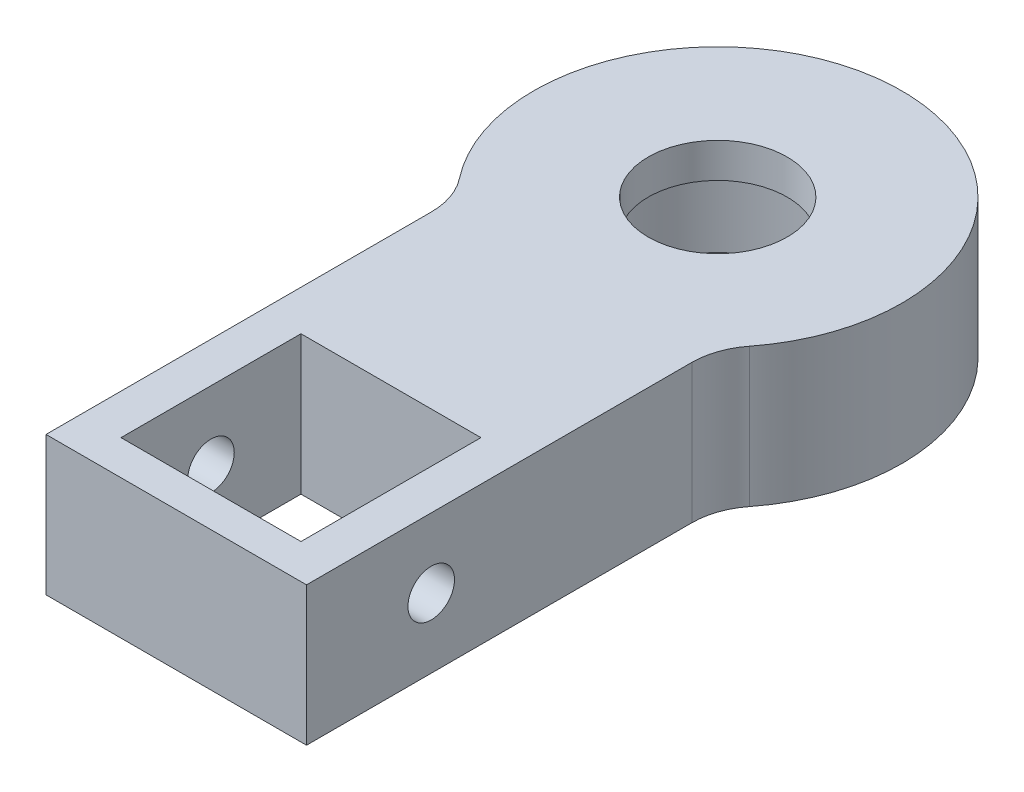
SolidWorks part; units mm, degrees
ref_plane "Front Plane" through (0, 0, 0) normal (0, 0, 1) x (1, 0, 0)
ref_plane "Top Plane" through (0, 0, 0) normal (0, 1, 0) x (1, 0, 0)
ref_plane "Right Plane" through (0, 0, 0) normal (1, 0, 0) x (0, 0, -1)
sketch "Sketch1" plane through (0, 0, 0) normal (0, 1, 0) x (1, 0, 0)
  line L1 (-12.954, -72.954) -> (12.954, -72.954)
  line L2 (-12.954, -72.954) -> (-12.954, -47.046)
  line L3 (-12.954, -47.046) -> (12.954, -47.046)
  line L4 (12.954, -72.954) -> (12.954, -47.046)
  line L5 (-12.954, -72.954) -> (12.954, -47.046) construction
  line L6 (-12.954, -47.046) -> (12.954, -72.954) construction
  line L7 (-18.754, -77.954) -> (18.754, -77.954)
  line L8 (-18.754, -77.954) -> (-18.754, -18.7226)
  line L10 (18.754, -77.954) -> (18.754, -18.7226)
  circle A0 centre (0, 0) radius 18.5
  arc A1 (-18.754, -18.7226) -> (18.754, -18.7226) centre (0, 0) cw
  point P3 (0, -60)
  point P9 (-16.6265, -20.6351)
  point P10 (0, -60)
  point P13 (17.954, -20.0656)
  point P15 (-17.954, -21.4469)
  point P16 (0, 0)
  point P17 (0, 0)
  dimension "D1" = 37
  dimension "D2" = 25.908
  dimension "D3" = 60
  dimension "D4" = 5.8
  dimension "D5" = 8
  dimension "D6" = 5.8
  dimension "D7" = 5
extrude "Boss-Extrude1" add sketch "Sketch1" along normal mid plane 20
sketch "Sketch2" plane through (0, 10, 0) normal (0, 1, 0) x (1, 0, 0)
  circle A0 centre (0, 0) radius 10
  circle A1 centre (0, 0) radius 26.5
  dimension "D1" = 20
extrude "Boss-Extrude2" add sketch "Sketch2" against normal blind 5
sketch "Sketch3" plane through (0, 0, 0) normal (0, 1, 0) x (1, 0, 0)
  line L0 (-24.4942, -60) -> (24.4942, -60) construction
  line L1 (0, 0) -> (0, -84.846) construction
  line L2 (12.954, -47.046) -> (-12.954, -47.046) construction
  line L3 (-12.954, -72.954) -> (12.954, -72.954) construction
  line L5 (-20.6245, -60) -> (21.6861, -60)
  line L6 (-20.6245, -60) -> (-20.6245, -56.65)
  line L7 (-20.6245, -56.65) -> (21.6861, -56.65)
  line L8 (21.6861, -60) -> (21.6861, -56.65)
  dimension "D1" = 3.35
revolve "Cut-Revolve1" cut sketch "Sketch3" angle 360 about L0
fillet "Fillet1" radius 10 2 edges at (-18.754, 0, 18.7226) (18.754, 0, 18.7226)
equation "\"D6@Sketch1\"=\"D4@Sketch1\""
